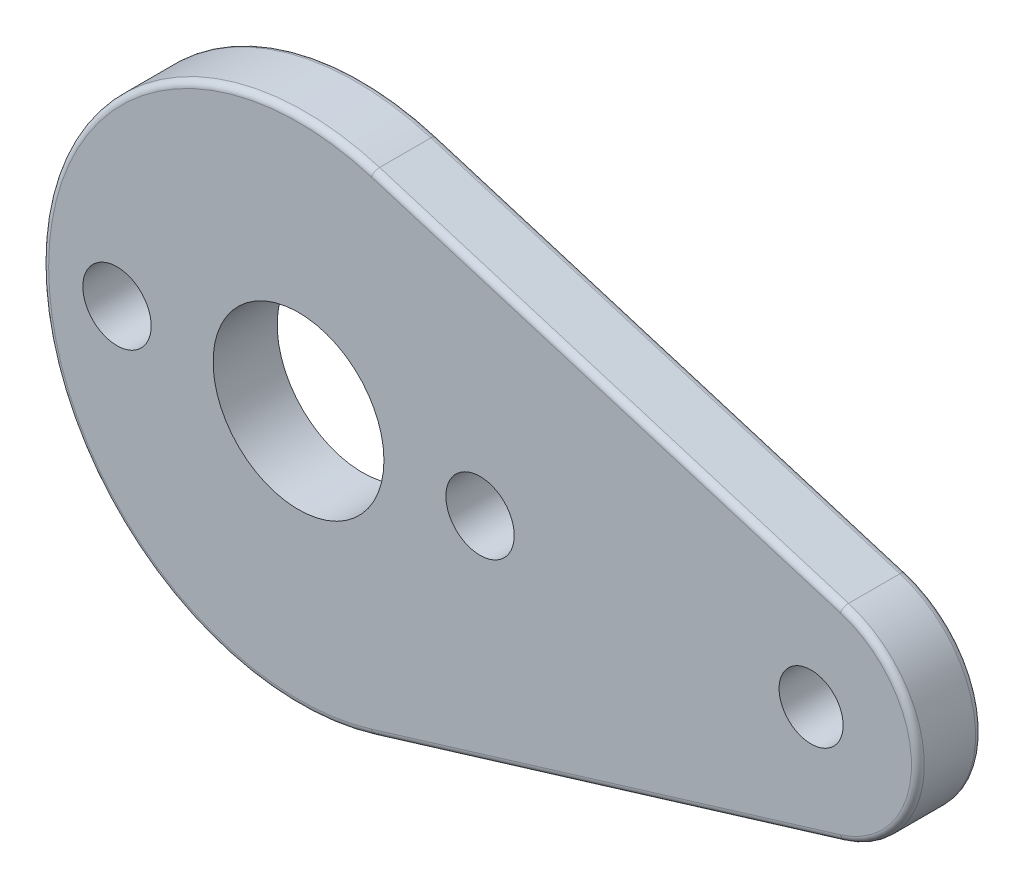
SolidWorks part; units mm, degrees
material "ABS"
ref_plane "Front" through (0, 0, 0) normal (0, 0, 1) x (1, 0, 0)
ref_plane "Top" through (0, 0, 0) normal (0, 1, 0) x (1, 0, 0)
ref_plane "Right" through (0, 0, 0) normal (1, 0, 0) x (0, 0, -1)
sketch "Esquisse1" plane through (0, 0, 0) normal (0, 0, 1) x (1, 0, 0)
  line L0 (3.5, 11.4782) -> (25.4583, 4.7826)
  line L1 (25.4583, -4.7826) -> (3.5, -11.4782)
  line L2 (0, -50) -> (0, 50) construction
  circle A0 centre (0, 0) radius 4
  circle A1 centre (24, 0) radius 1.5
  arc A2 (25.4583, 4.7826) -> (25.4583, -4.7826) centre (24, 0) cw
  arc A3 (3.5, -11.4782) -> (3.5, 11.4782) centre (0, 0) cw
  circle A4 centre (-8.5, 0) radius 1.6
  circle A5 centre (8.5, 0) radius 1.6
  dimension "D1" = 3
  dimension "D2" = 8
  dimension "D3" = 24
  dimension "D4" = 5
  dimension "D5" = 12
  dimension "D6" = 3.2
  dimension "D7" = 17
extrude "Boss.-Extru.1" add sketch "Esquisse1" along normal blind 3
fillet "Congé2" radius 0.3 8 edges at (-12, 0, 0) (14.4792, 8.1304, 0) (29, 0, 0) (14.4792, 8.1304, 3) (-12, 0, 3) (14.4792, -8.1304, 0) (14.4792, -8.1304, 3) (29, 0, 3)
